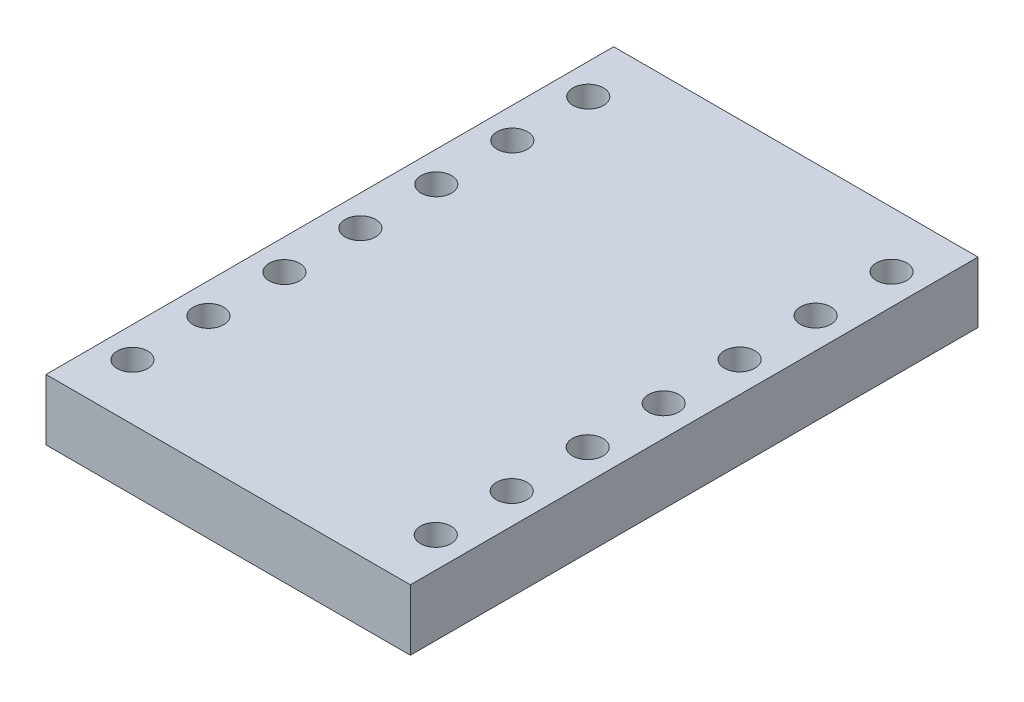
SolidWorks part; units mm, degrees
material "6061-T6 (SS)"
ref_plane "Front Plane" through (0, 0, 0) normal (0, 0, 1) x (1, 0, 0)
ref_plane "Top Plane" through (0, 0, 0) normal (0, 1, 0) x (1, 0, 0)
ref_plane "Right Plane" through (0, 0, 0) normal (1, 0, 0) x (0, 0, -1)
sketch "Sketch1" plane through (0, 0, 0) normal (0, 1, 0) x (1, 0, 0)
  line L1 (0, 0) -> (10, 0)
  line L2 (0, 0) -> (0, -63)
  line L3 (0, -63) -> (10, -63)
  line L4 (10, 0) -> (10, -63)
  dimension "D1" = 63
  dimension "D2" = 10
extrude "Boss-Extrude1" add sketch "Sketch1" along normal blind 10
sketch "Sketch2" plane through (0, 10, 0) normal (0, 1, 0) x (1, 0, 0)
  line L0 (0, 0) -> (10, -63) construction
  line L1 (10, 0) -> (0, -63) construction
  line L4 (34.845, -78) -> (-24.845, -78)
  line L5 (34.845, -78) -> (34.845, 15)
  line L6 (34.845, 15) -> (-24.845, 15)
  line L7 (-24.845, -78) -> (-24.845, 15)
  line L8 (34.845, -78) -> (-24.845, 15) construction
  line L9 (34.845, 15) -> (-24.845, -78) construction
  circle A0 centre (-19.845, 5.838) radius 2.5
  circle A1 centre (-19.845, -6.608) radius 2.5
  circle A2 centre (-19.845, -19.054) radius 2.5
  circle A3 centre (-19.845, -31.5) radius 2.5
  circle A4 centre (-19.845, -43.946) radius 2.5
  circle A5 centre (-19.845, -56.392) radius 2.5
  circle A6 centre (-19.845, -68.838) radius 2.5
  circle A7 centre (29.845, 5.838) radius 2.5
  circle A8 centre (29.845, -6.608) radius 2.5
  circle A9 centre (29.845, -19.054) radius 2.5
  circle A10 centre (29.845, -31.5) radius 2.5
  circle A11 centre (29.845, -43.946) radius 2.5
  circle A12 centre (29.845, -56.392) radius 2.5
  circle A13 centre (29.845, -68.838) radius 2.5
  point P6 (5, -31.5)
  dimension "D3" = 5
  dimension "D4" = 9.162
  dimension "D5" = 5
  dimension "D7" = 5
  dimension "D8" = 5
  dimension "D10" = 12.446
  dimension "D1" = 93
  dimension "D2" = 59.69
  dimension "D6" = 7
  dimension "D9" = 7
extrude "Boss-Extrude2" add sketch "Sketch2" along normal blind 10
sketch "Sketch3" plane through (0, 0, 0) normal (-1, 0, 0) x (0, 0, 1)
  line L0 (0, 10) -> (0, 0) construction
  circle A0 centre (12.75, 5) radius 2.75
  circle A1 centre (25.196, 5) radius 2.75
  circle A2 centre (37.642, 5) radius 2.75
  circle A3 centre (50.088, 5) radius 2.75
  dimension "D1" = 12.75
  dimension "D2" = 5.5
  dimension "D3" = 4
extrude "Cut-Extrude1" cut sketch "Sketch3" against normal through all
sketch "Sketch4" plane through (0, 10, 0) normal (0, -1, 0) x (-1, 0, 0)
  line L0 (24.845, -78) -> (-34.845, -78) construction
  line L1 (0, -78) -> (-10, -78)
  line L2 (0, -78) -> (0, 14.3732)
  line L3 (0, 14.3732) -> (-10, 14.3732)
  line L4 (-10, -78) -> (-10, 14.3732)
  line L5 (-10, -63) -> (-10, 0) construction
  dimension "D1" = 10
  dimension "D2" = 0
